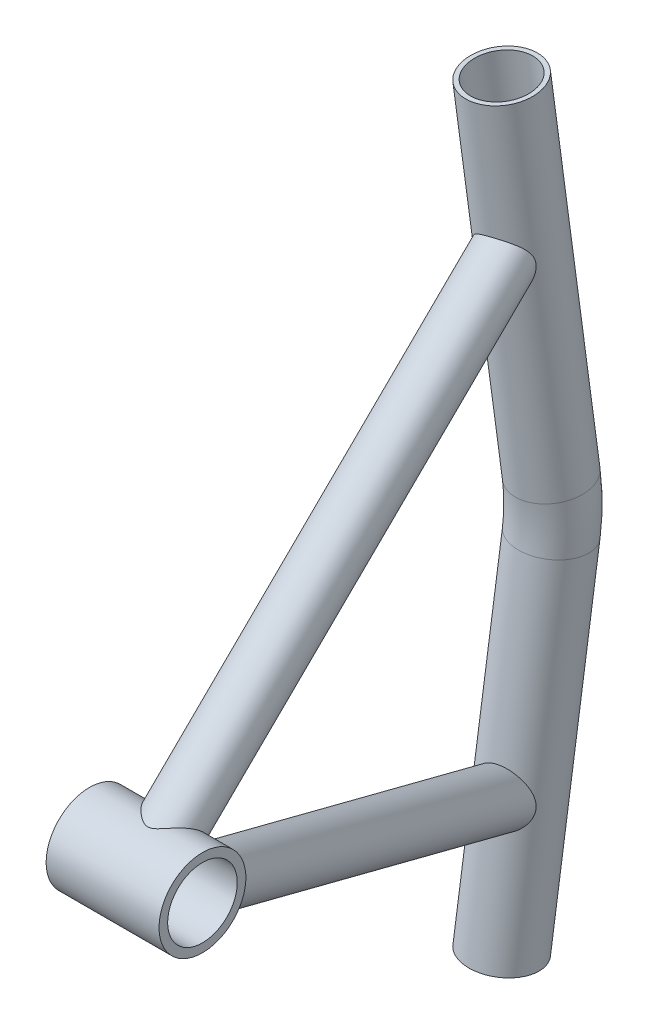
SolidWorks part; units mm, degrees
material "AISI 4130 Steel, normalized at 870C"
ref_plane "X-Y Datum" through (0, 0, 0) normal (0, 0, 1) x (1, 0, 0)
ref_plane "X-Z Datum" through (0, 0, 0) normal (0, 1, 0) x (1, 0, 0)
ref_plane "Y-Z Datum" through (0, 0, 0) normal (1, 0, 0) x (0, 0, -1)
ref_plane "FRH Reference" through (-89.8073, 0, -36.2845) normal (0.9272, 0, 0.3746) x (0.3746, 0, -0.9272)
sketch "Sketch6" plane through (0, 0, 0) normal (0, 1, 0) x (1, 0, 0)
  line L1 (20.6375, 15.875) -> (-20.6375, 15.875)
  line L2 (20.6375, 15.875) -> (20.6375, 12.7254)
  line L3 (20.6375, 12.7254) -> (-20.6375, 12.7254)
  line L4 (-20.6375, 15.875) -> (-20.6375, 12.7254)
  line L9 (-66.7868, 0) -> (90.4215, 0) construction
revolve "Revolve2" add sketch "Sketch6" angle 360 about L9
sketch3d "3DSketch2"
  line L0 (0, 0, 0) -> (0, 11.2253, -11.2253) construction
  line L1 (-66.7868, 0, 0) -> (90.4215, 0, 0) construction
  line L2 (0, 0, 0) -> (0, 0, 15.875) construction
  line L3 (0, 0, 0) -> (0, 0, -15.875) construction
  line L4 (0, 0, 0) -> (0, -11.2253, -11.2253) construction
  line L7 (20.6375, 0, -15.875) -> (-20.6375, 0, -15.875) construction
  line L8 (0, 11.2253, -11.2253) -> (-45.6789, 89.2363, -182.5965)
  line L9 (0, -11.2253, -11.2253) -> (-45.6789, -89.2363, -182.5965)
  line L10 (-47.9371, 138.4715, -177.9436) -> (-42.012, 9.2876, -190.1521)
  line L11 (-42.012, -9.2876, -190.1521) -> (-47.9371, -138.4715, -177.9436)
  line L12 (0, 0, 0) -> (86.995, 0, 0) construction
  arc A0 (-42.012, 9.2876, -190.1521) -> (-42.012, -9.2876, -190.1521) centre (-80.6149, 0, -110.6111) ccw
  point P20 (-160.5935, 0, -149.4264)
  dimension "D1" = 45
  dimension "D2" = 135
  dimension "D3" = 45
  dimension "D4" = 135
  dimension "D5" = 193.7534
  dimension "D7" = 47.485
  dimension "D6" = 155.523
  dimension "D8" = 86.995
  dimension "D9" = 155.523
ref_plane "Plane1" through (-45.6789, 89.2363, -182.5965) normal (-0.2358, 0.4026, -0.8845) x (-0.9718, -0.0977, 0.2146)
sketch "Sketch10" plane through (-45.6789, 89.2363, -182.5965) normal (-0.2358, 0.4026, -0.8845) x (-0.9718, -0.0977, 0.2146)
  circle A0 centre (0, 0) radius 9.525
  circle A1 centre (0, 0) radius 7.874
  dimension "D1" = 19.05
  dimension "D2" = 1.651
extrude "Boss-Extrude1" add sketch "Sketch10" against normal up to surface (203.9812 mm away) separate body
ref_plane "Plane2" through (-45.6789, -89.2363, -182.5965) normal (-0.2358, -0.4026, -0.8845) x (-0.9718, 0.0977, 0.2146)
sketch "Sketch11" plane through (-45.6789, -89.2363, -182.5965) normal (-0.2358, -0.4026, -0.8845) x (-0.9718, 0.0977, 0.2146)
  circle A0 centre (0, 0) radius 9.525
  circle A1 centre (0, 0) radius 7.874
  dimension "D1" = 19.05
  dimension "D2" = 1.651
extrude "Boss-Extrude2" add sketch "Sketch11" against normal up to surface (193.2326 mm away) separate body
ref_plane "Plane3" through (-47.9371, -138.4715, -177.9436) normal (-0.0456, -0.9945, 0.094) x (-0.999, 0.0454, -0.0043)
sketch "Sketch12" plane through (-47.9371, -138.4715, -177.9436) normal (-0.0456, -0.9945, 0.094) x (-0.999, 0.0454, -0.0043)
  circle A0 centre (0, 0) radius 12.7
  dimension "D1" = 25.4
sweep "Cut-Sweep1" cut profiles "Sketch12" path "3DSketch2"
ref_plane "Plane4" through (-108.6951, 0, -52.752) normal (0.8996, 0, 0.4366) x (0.4366, 0, -0.8996)
sketch "Sketch14" plane through (-108.6951, 0, -52.752) normal (0.8996, 0, 0.4366) x (0.4366, 0, -0.8996)
  line L0 (139.1563, 138.4715) -> (152.7267, 9.2876)
  line L1 (152.7267, -9.2876) -> (139.1563, -138.4715)
  arc A0 (152.7267, 9.2876) -> (152.7267, -9.2876) centre (64.3131, 0) cw
sketch "Sketch15" plane through (-47.9371, -138.4715, -177.9436) normal (-0.0456, -0.9945, 0.094) x (-0.999, 0.0454, -0.0043)
  circle A0 centre (0, 0) radius 12.7
  circle A1 centre (0, 0) radius 11.049
  dimension "D1" = 25.4
  dimension "D2" = 1.651
sweep "Sweep2" add profiles "Sketch15" path "Sketch14"
equation "\"Tube_Thickness\"=0.75"
equation "\"Wall_Thickness\"=0.065"
